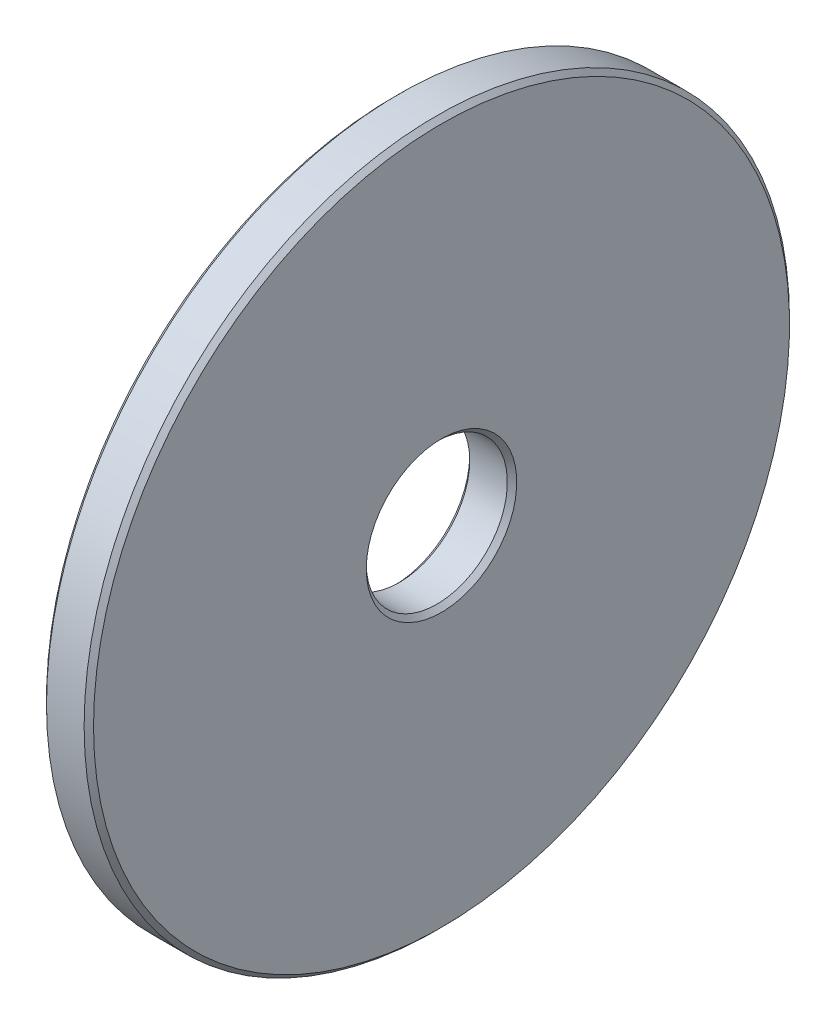
SolidWorks part; units mm, degrees
ref_plane "前视基准面" through (0, 0, 0) normal (0, 0, 1) x (1, 0, 0)
ref_plane "上视基准面" through (0, 0, 0) normal (0, 1, 0) x (1, 0, 0)
ref_plane "右视基准面" through (0, 0, 0) normal (1, 0, 0) x (0, 0, -1)
sketch "草图1" plane through (0, 0, 0) normal (0, 0, 1) x (1, 0, 0)
  line L0 (-11.6247, 0) -> (14.2359, 0) construction
  line L1 (0, 14.738) -> (0, -16.4955) construction
  line L2 (0, 1.5) -> (0, 7.5)
  line L3 (0, 7.5) -> (-1, 7.5)
  line L4 (-1, 7.5) -> (-1, 1.5)
  line L5 (-1, 1.5) -> (0, 1.5)
  dimension "D1" = 3
  dimension "D2" = 15
  dimension "D3" = 1
revolve "旋转1" add sketch "草图1" angle 360 about L0
chamfer "倒角1" distance 0.1 angle 45 4 edges at (-1, 0, 1.5) (0, 0, 1.5) (0, 0, 7.5) (-1, 0, 7.5)
